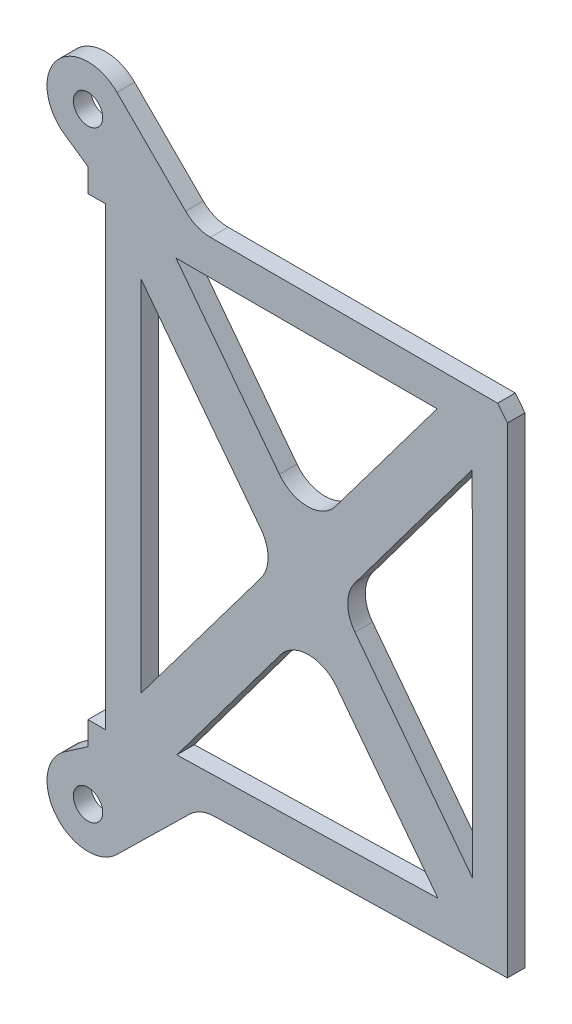
SolidWorks part; units mm, degrees
ref_plane "前视基准面" through (0, 0, 0) normal (0, 0, 1) x (1, 0, 0)
ref_plane "上视基准面" through (0, 0, 0) normal (0, 1, 0) x (1, 0, 0)
ref_plane "右视基准面" through (0, 0, 0) normal (1, 0, 0) x (0, 0, -1)
sketch "Model" plane through (0, 0, 0) normal (0, 0, 1) x (1, 0, 0)
  line L0 (575.2026, 450.0716) -> (599.7026, 450.0716)
  line L1 (575.4819, 407.4632) -> (600.5349, 408.0225)
  line L2 (600.5349, 449.0225) -> (600.5349, 408.0225)
  line L3 (572.2602, 447.0716) -> (594.5349, 447.0716)
  line L4 (572.3339, 410.4032) -> (594.6092, 410.9505)
  line L5 (597.5349, 444.0717) -> (597.5356, 413.9497)
  line L6 (569.2602, 444.0716) -> (569.2602, 413.4023)
  line L7 (569.2602, 444.0716) -> (579.5009, 430.6911)
  line L8 (572.2602, 447.0716) -> (581.0844, 435.508)
  line L9 (569.2602, 413.4023) -> (579.5178, 427.0668)
  line L10 (572.3339, 410.4032) -> (581.1797, 422.2211)
  line L11 (594.5349, 447.0716) -> (585.8686, 435.5269)
  line L12 (585.9638, 422.2467) -> (594.6092, 410.9505)
  line L13 (597.5349, 444.0717) -> (587.5118, 430.6808)
  line L14 (597.5356, 413.9497) -> (587.5286, 427.0632)
  line L15 (564.7602, 409.2238) -> (564.7602, 407.2238)
  line L16 (564.7602, 448.0716) -> (564.7602, 450.0716)
  line L17 (564.7602, 448.0716) -> (566.2602, 448.0716)
  line L18 (564.7602, 409.2238) -> (566.2602, 409.2238)
  line L19 (566.2602, 409.2238) -> (566.2602, 448.0716)
  line L20 (567.2351, 400.499) -> (568.4555, 401.6957)
  line L21 (568.4555, 401.6957) -> (573.4276, 406.5715)
  line L22 (564.7602, 407.2238) -> (562.7748, 405.8562)
  line L23 (567.2351, 456.7965) -> (573.0813, 450.9503)
  line L24 (564.7602, 450.0716) -> (562.7748, 451.4392)
  line L25 (599.7026, 450.0716) -> (600.5349, 449.0225)
  circle A0 centre (564.7602, 454.3216) radius 1.25
  circle A1 centre (564.7602, 402.9738) radius 1.25
  circle A2 centre (564.7602, 454.3216) radius 1.25
  arc A3 (573.0813, 450.9503) -> (575.2026, 450.0716) centre (575.2026, 453.0716) ccw
  arc A4 (575.4819, 407.4632) -> (573.4276, 406.5715) centre (575.6052, 404.3668) ccw
  circle A5 centre (564.7602, 402.9738) radius 1.25
  arc A6 (579.5178, 427.0668) -> (579.5009, 430.6911) centre (577.1186, 428.8678) ccw
  arc A7 (581.0844, 435.508) -> (585.8686, 435.5269) centre (583.4694, 437.3279) ccw
  arc A8 (585.9638, 422.2467) -> (581.1797, 422.2211) centre (583.5814, 420.4234) ccw
  arc A9 (587.5118, 430.6808) -> (587.5286, 427.0632) centre (589.9136, 428.8831) ccw
  arc A10 (562.7748, 405.8562) -> (567.2351, 400.499) centre (564.7602, 402.9738) ccw
  arc A11 (567.2351, 456.7965) -> (562.7748, 451.4392) centre (564.7602, 454.3216) ccw
  circle A12 centre (564.7602, 454.3216) radius 1.25
  circle A13 centre (564.7602, 402.9738) radius 1.25
  circle A14 centre (564.7602, 454.3216) radius 1.25
  circle A15 centre (564.7602, 454.3216) radius 1.25
  circle A16 centre (564.7602, 402.9738) radius 1.25
extrude "凸台-拉伸2" add sketch "Model" along normal blind 1.5 contours L23 A11 L24 L16 L17 L19 L18 L15 L22 A10 L20 L21 A4 L1 L2 L25 L0 A3 A0 A1 A6 L9 L6 L7 A7 L8 L3 L11 A8 L12 L4 L10 A9 L13 L5 L14
